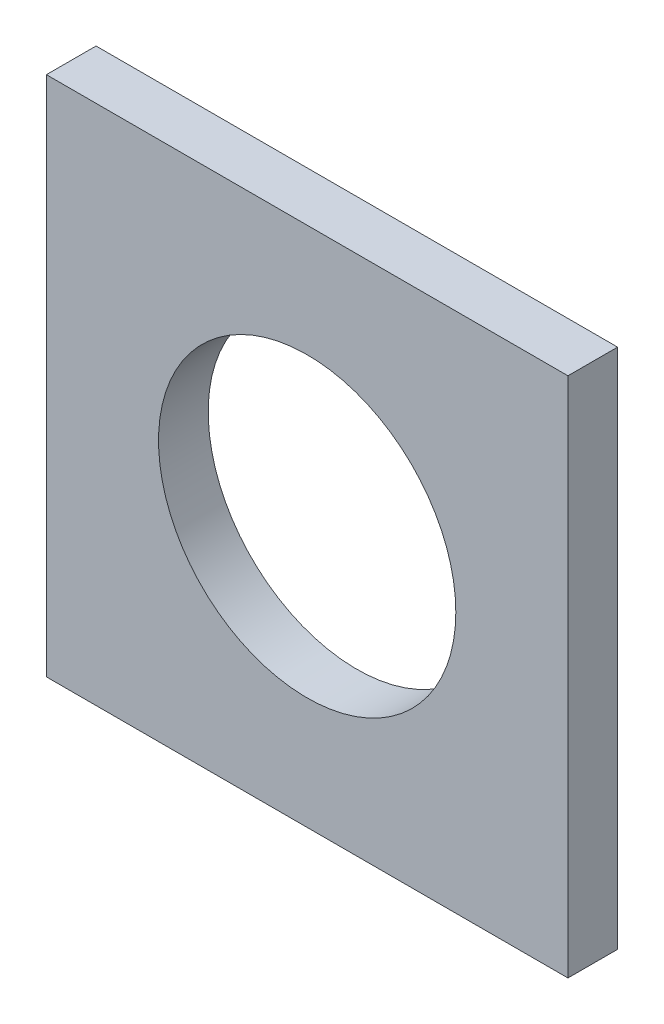
SolidWorks part; units mm, degrees
ref_plane "Plano frontal" through (0, 0, 0) normal (0, 0, 1) x (1, 0, 0)
ref_plane "Plano superior" through (0, 0, 0) normal (0, 1, 0) x (1, 0, 0)
ref_plane "Plano direito" through (0, 0, 0) normal (1, 0, 0) x (0, 0, -1)
sketch "Esboço1" plane through (0, 0, 0) normal (0, 0, 1) x (1, 0, 0)
  line L0 (-25, -25) -> (-25, 25)
  line L1 (-25, -25) -> (25, -25)
  line L2 (-25, 25) -> (25, 25)
  line L3 (25, -25) -> (25, 25)
  line L4 (-25, -25) -> (25, 25) construction
  line L5 (-25, 25) -> (25, -25) construction
  circle A0 centre (0, 0) radius 14.25
  dimension "D3" = 28.5
  dimension "D1" = 50
  dimension "D2" = 50
extrude "Ressalto-extrusão1" add sketch "Esboço1" along normal blind 4.76
